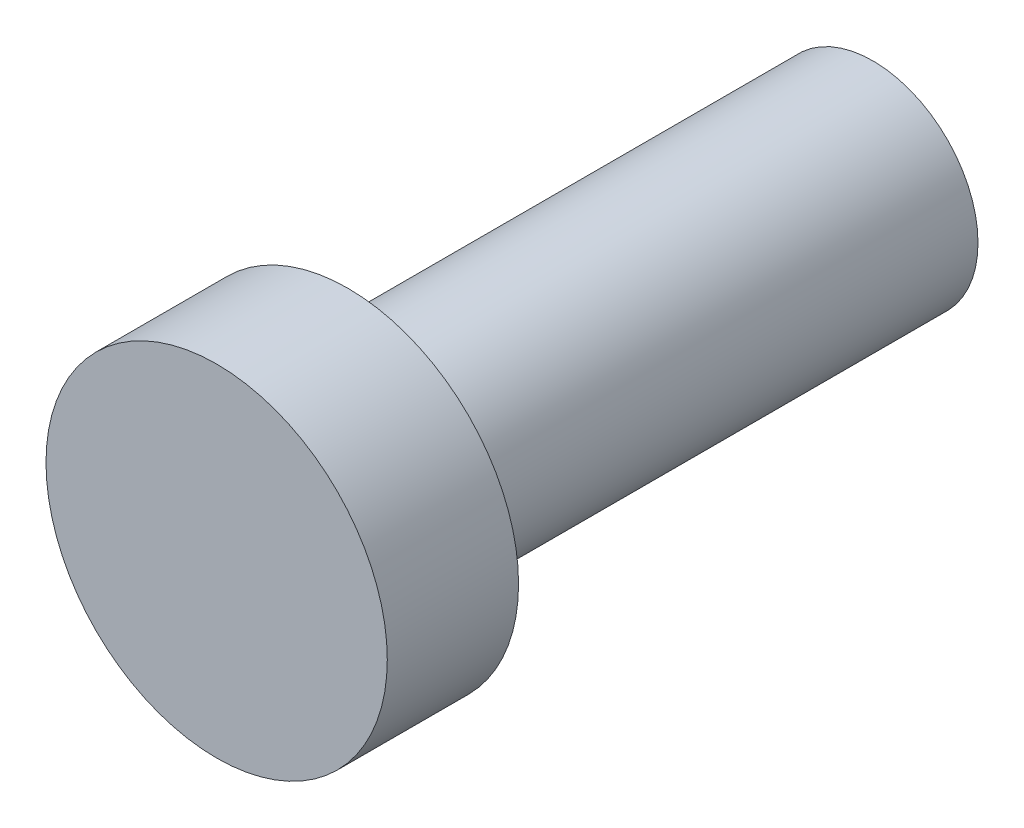
SolidWorks part; units mm, degrees
ref_plane "Plan de face" through (0, 0, 0) normal (0, 0, 1) x (1, 0, 0)
ref_plane "Plan de dessus" through (0, 0, 0) normal (0, 1, 0) x (1, 0, 0)
ref_plane "Plan de droite" through (0, 0, 0) normal (1, 0, 0) x (0, 0, -1)
sketch "Esquisse1" plane through (0, 0, 0) normal (0, 0, 1) x (1, 0, 0)
  circle A0 centre (0, 0) radius 4
  dimension "D1" = 8
extrude "Boss.-Extru.1" add sketch "Esquisse1" along normal blind 20
sketch "Esquisse2" plane through (0, 0, 20) normal (0, 0, 1) x (1, 0, 0)
  circle A0 centre (0, 0) radius 6.5
  dimension "D1" = 13
extrude "Boss.-Extru.2" add sketch "Esquisse2" along normal blind 5
